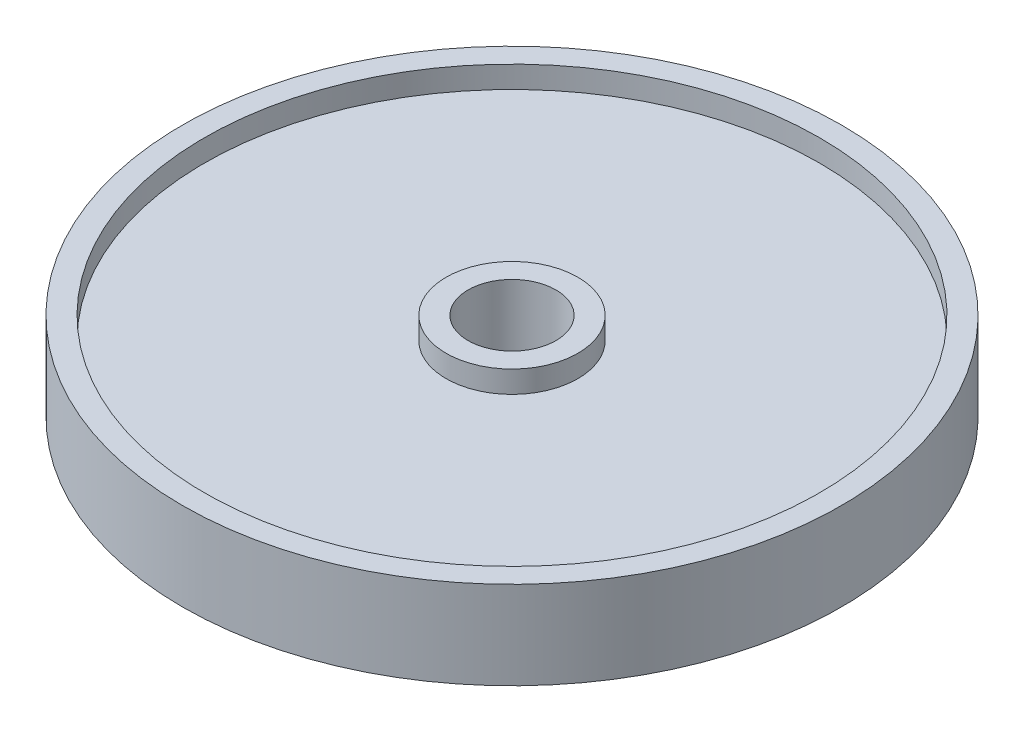
SolidWorks part; units mm, degrees
ref_plane "Front" through (0, 0, 0) normal (0, 0, 1) x (1, 0, 0)
ref_plane "Top" through (0, 0, 0) normal (0, 1, 0) x (1, 0, 0)
ref_plane "Right" through (0, 0, 0) normal (1, 0, 0) x (0, 0, -1)
other "Configuration Table"
sketch "Sketch1" plane through (0, 0, 0) normal (0, 0, 1) x (1, 0, 0)
  line L0 (0, -9.4822) -> (0, 10.4805) construction
  line L1 (5, -17.5) -> (5, 17.5) construction
  line L2 (5, 5) -> (7.5, 5)
  line L3 (5, 5) -> (5, -5)
  line L4 (5, -5) -> (7.5, -5)
  line L5 (37.5, 5) -> (37.5, -5)
  line L6 (7.5, 2.5) -> (35, 2.5)
  line L7 (35, 5) -> (35, 2.5)
  line L8 (7.5, -2.5) -> (35, -2.5)
  line L9 (7.5, 5) -> (7.5, 2.5)
  line L10 (35, 5) -> (37.5, 5)
  line L11 (35, -5) -> (37.5, -5)
  line L12 (35, -2.5) -> (35, -5)
  line L13 (7.5, -2.5) -> (7.5, -5)
  point P9 (5, 0)
  dimension "D1" = 10
  dimension "D2" = 75
  dimension "D3" = 2.5
revolve "Revolve1" add sketch "Sketch1" angle 360 about L0
